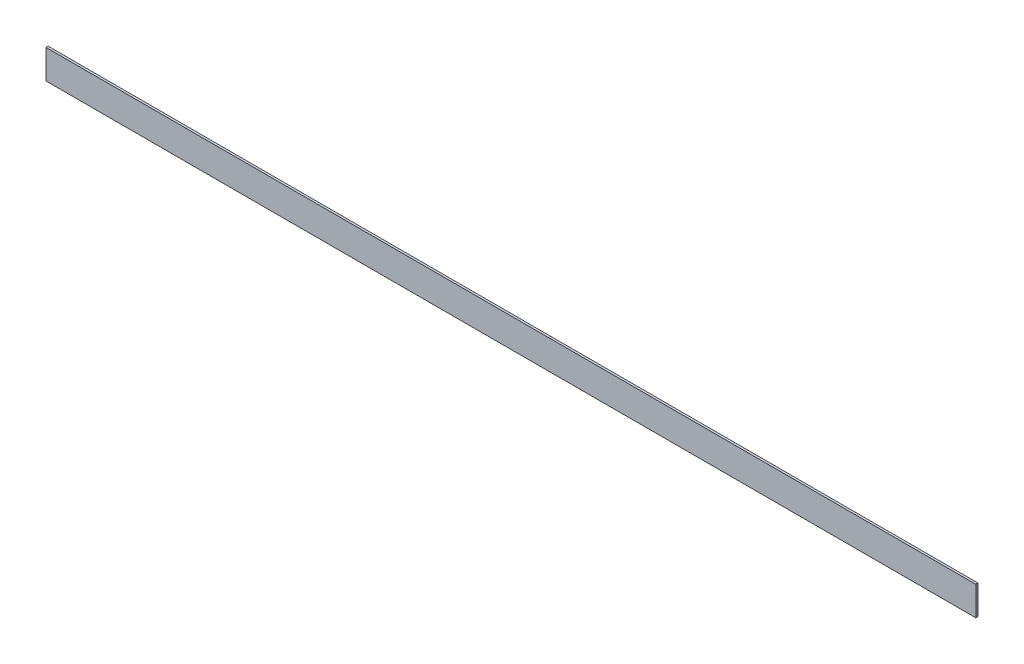
SolidWorks part; units mm, degrees
ref_plane "Front Plane" through (0, 0, 0) normal (0, 0, 1) x (1, 0, 0)
ref_plane "Top Plane" through (0, 0, 0) normal (0, 1, 0) x (1, 0, 0)
ref_plane "Right Plane" through (0, 0, 0) normal (1, 0, 0) x (0, 0, -1)
other "Configuration Table"
sketch "Sketch1" plane through (0, 0, 0) normal (0, 0, 1) x (1, 0, 0)
  line L1 (30, 1950) -> (670, 1950)
  line L2 (30, 1950) -> (30, 1970)
  line L3 (30, 1970) -> (670, 1970)
  line L4 (670, 1950) -> (670, 1970)
extrude "TOPPING_panel_ust_serit_1" add sketch "Sketch1" along normal blind 1.5 from offset 38.5 separate body
